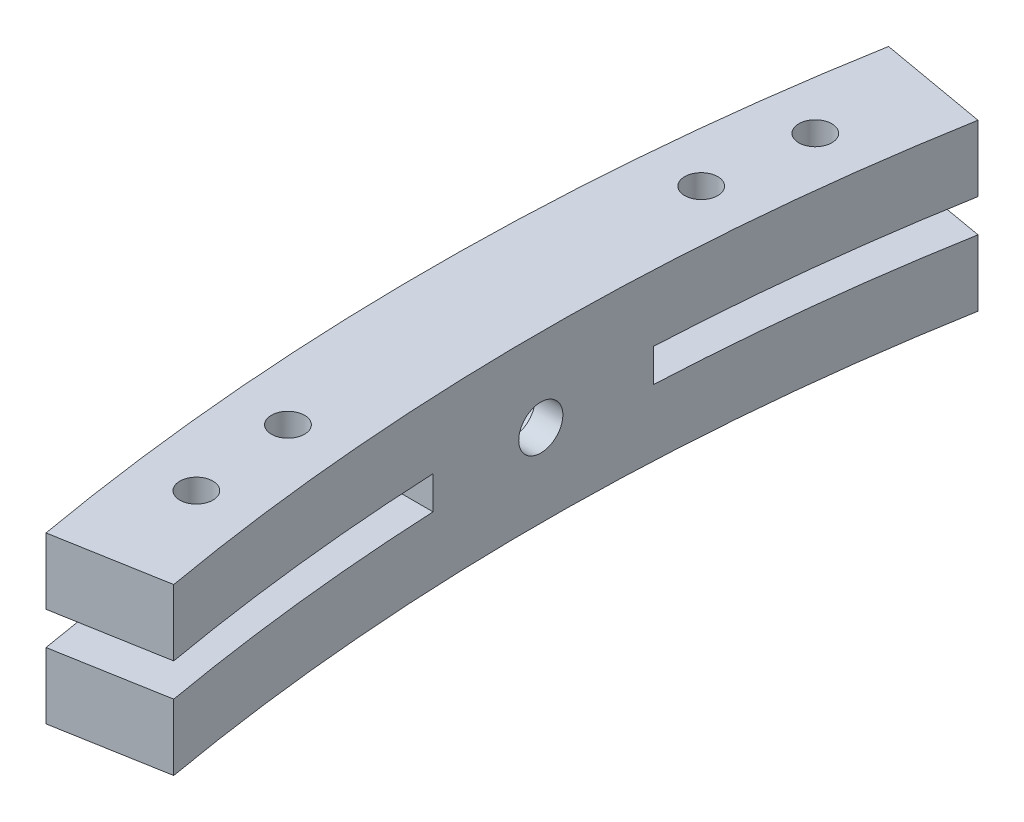
SolidWorks part; units mm, degrees
ref_plane "Front Plane" through (0, 0, 0) normal (0, 0, 1) x (1, 0, 0)
ref_plane "Top Plane" through (0, 0, 0) normal (0, 1, 0) x (1, 0, 0)
ref_plane "Right Plane" through (0, 0, 0) normal (1, 0, 0) x (0, 0, -1)
sketch "Sketch1" plane through (0, 0, 0) normal (0, 0, 1) x (1, 0, 0)
  line L0 (190, 0) -> (-190, 0) construction
  line L1 (0, 190) -> (0, -190) construction
  line L2 (0, 0) -> (-187.1135, 32.9932) construction
  line L3 (0, 0) -> (-187.1135, -32.9932) construction
  line L4 (-187.1135, 32.9932) -> (-196.9616, 34.7296)
  line L5 (-187.1135, -32.9932) -> (-196.9616, -34.7296)
  arc A0 (-187.1135, 32.9932) -> (-187.1135, -32.9932) centre (0, 0) ccw
  arc A1 (-196.9616, 34.7296) -> (-196.9616, -34.7296) centre (0, 0) ccw
  circle A3 centre (0, 0) radius 190 construction
  dimension "D1" = 380
  dimension "D2" = 10
  dimension "D3" = 20
sketch "Sketch9" plane through (0, 0, 0) normal (0, 1, 0) x (1, 0, 0)
  line L0 (0, 0) -> (-196.9616, 34.7296)
  line L1 (-200, 0) -> (200, 0) construction
  line L2 (0, 0) -> (-196.9616, -34.7296)
  circle A0 centre (0, 0) radius 195 construction
  circle A1 centre (0, 0) radius 195 construction
  circle A8 centre (0, 0) radius 200 construction
  circle A9 centre (0, 0) radius 190 construction
  circle A10 centre (0, 0) radius 200
  circle A11 centre (0, 0) radius 190
  dimension "D1" = 20
extrude "base" [suppressed] add sketch "Sketch9" along normal mid plane 15 contours A11 L0 A10 L2
sketch "Sketch11" [suppressed] plane through (0, 0, 0) normal (0, 1, 0) x (1, 0, 0)
  line L8 (-189.7367, -10) -> (-199.7498, -10) construction
  line L9 (-187.1135, -32.9932) -> (-196.9616, -34.7296) construction
  line L10 (-189.7367, 10) -> (-199.7498, 10) construction
  line L11 (-187.1135, 32.9932) -> (-196.9616, 34.7296) construction
  line L12 (-189.7367, -10) -> (-199.7498, -10)
  line L13 (-187.1135, -32.9932) -> (-196.9616, -34.7296)
  line L14 (-189.7367, 10) -> (-199.7498, 10)
  line L15 (-187.1135, 32.9932) -> (-196.9616, 34.7296)
  circle A14 centre (0, 0) radius 200 construction
  circle A15 centre (0, 0) radius 190 construction
  arc A16 (-196.9616, 34.7296) -> (-199.7498, 10) centre (0, 0) ccw
  arc A17 (-187.1135, 32.9932) -> (-189.7367, 10) centre (0, 0) ccw
  arc A18 (-199.7498, -10) -> (-196.9616, -34.7296) centre (0, 0) ccw
  arc A19 (-189.7367, -10) -> (-187.1135, -32.9932) centre (0, 0) ccw
extrude "Cut-Extrude8" [suppressed] cut sketch "Sketch11" along normal up to surface and the other way up to surface
sketch "Sketch12" plane through (0, 0, 0) normal (0, 1, 0) x (1, 0, 0)
  line L0 (-200, 0) -> (200, 0) construction
  line L1 (-200, 0) -> (200, 0) construction
  circle A0 centre (0, 0) radius 195 construction
  circle A1 centre (0, 0) radius 195 construction
  circle A2 centre (-193.3908, 25) radius 1.5
  circle A3 centre (-194.4222, 15) radius 1.5
  circle A4 centre (-194.4222, -15) radius 1.5
  circle A5 centre (-193.3908, -25) radius 1.5
  dimension "D1" = 3
  dimension "D2" = 30
  dimension "D3" = 50
extrude "Cut-Extrude9" [suppressed] cut sketch "Sketch12" against normal through all both and the other way through all
sketch "Sketch13" plane through (0, 0, 0) normal (0, 1, 0) x (1, 0, 0)
  line L2 (0, 0) -> (-216.6577, 38.2026)
  line L4 (-215, 0) -> (215, 0) construction
  line L5 (-215, 0) -> (215, 0) construction
  line L6 (0, 0) -> (-216.6577, -38.2026)
  line L7 (-209.7618, -10) -> (-219.7726, -10) construction
  line L8 (-209.7618, 10) -> (-219.7726, 10) construction
  line L9 (-209.7618, -10) -> (-219.7726, -10)
  line L10 (-209.7618, 10) -> (-219.7726, 10)
  circle A5 centre (0, 0) radius 215 construction
  circle A6 centre (0, 0) radius 220 construction
  circle A7 centre (0, 0) radius 210 construction
  circle A8 centre (0, 0) radius 220
  circle A9 centre (0, 0) radius 210
  dimension "D1" = 20
extrude "base2" add sketch "Sketch13" along normal mid plane 15 contours A9 L2 A8 L10 | A9 L10 A8 L9 | A9 L9 A8 L6
sketch "Sketch14" plane through (0, 0, 0) normal (0, 1, 0) x (1, 0, 0)
  line L0 (-209.7618, -10) -> (-219.7726, -10) construction
  line L1 (-209.7618, 10) -> (-219.7726, 10) construction
  line L2 (-209.7618, -10) -> (-219.7726, -10)
  line L3 (-209.7618, 10) -> (-219.7726, 10)
  line L4 (0, 0) -> (-216.6577, 38.2026) construction
  line L5 (0, 0) -> (-216.6577, -38.2026) construction
  line L6 (-206.8096, 36.4661) -> (-216.6577, 38.2026)
  line L7 (-206.8096, -36.4661) -> (-216.6577, -38.2026)
  arc A0 (-219.7726, -10) -> (-216.6577, -38.2026) centre (0, 0) ccw
  arc A1 (-209.7618, -10) -> (-206.8096, -36.4661) centre (0, 0) ccw
  circle A4 centre (0, 0) radius 220 construction
  circle A5 centre (0, 0) radius 210 construction
  arc A6 (-216.6577, 38.2026) -> (-219.7726, 10) centre (0, 0) ccw
  arc A7 (-206.8096, 36.4661) -> (-209.7618, 10) centre (0, 0) ccw
extrude "mount2" cut sketch "Sketch14" along normal up to surface and the other way up to surface
sketch "Sketch16" plane through (0, 0, 0) normal (0, 1, 0) x (1, 0, 0)
  line L0 (-214.1819, 18.7385) -> (0, 0) construction
  line L1 (0, 0) -> (-213.1606, 28.0631) construction
  line L3 (0, 0) -> (-215, 0) construction
  line L4 (-214.1819, -18.7385) -> (0, 0) construction
  line L5 (0, 0) -> (-213.1606, -28.0631) construction
  circle A0 centre (0, 0) radius 215 construction
  circle A1 centre (0, 0) radius 215 construction
  circle A2 centre (-213.1606, 28.0631) radius 1.5
  circle A3 centre (-214.1819, 18.7385) radius 1.5
  circle A4 centre (-214.1819, -18.7385) radius 1.5
  circle A5 centre (-213.1606, -28.0631) radius 1.5
  dimension "D1" = 3
  dimension "D2" = 10
  dimension "D3" = 15
extrude "mount hole2" cut sketch "Sketch16" against normal through all both and the other way through all
ref_plane "shaft" through (-215, 0, 0) normal (1, 0, 0) x (0, 0, -1)
sketch "Sketch17" plane through (-215, 0, 0) normal (1, 0, 0) x (0, 0, -1)
  circle A0 centre (0, 0) radius 2
  dimension "D1" = 4
extrude "shaft hole" cut sketch "Sketch17" along normal through all
sketch "Sketch18" plane through (0, 0, 0) normal (0, 1, 0) x (1, 0, 0)
  line L1 (-215, 0) -> (-212.5, 0)
  line L16 (-215, 0) -> (-215, 3.5)
  line L17 (-215, 3.5) -> (-212.5, 3.5)
  line L18 (-212.5, 0) -> (-212.5, 3.5)
  point P0 (-215, 0)
  dimension "D1" = 2.5
  dimension "D2" = 3.5
revolve "bearinghole" cut sketch "Sketch18" angle 360 about L5
sketch "Sketch6" plane through (0, 0, 0) normal (0, 0, 1) x (1, 0, 0)
  line L1 (-208.5097, 7.5) -> (-171.4903, 7.5)
  line L2 (-208.5097, 7.5) -> (-208.5097, -7.5)
  line L3 (-208.5097, -7.5) -> (-171.4903, -7.5)
  line L4 (-171.4903, 7.5) -> (-171.4903, -7.5)
  line L5 (-208.5097, 7.5) -> (-171.4903, -7.5) construction
  line L6 (-208.5097, -7.5) -> (-171.4903, 7.5) construction
  arc A0 (-196.9616, 34.7296) -> (-196.9616, -34.7296) centre (0, 0) ccw construction
  arc A1 (-187.1135, 32.9932) -> (-187.1135, -32.9932) centre (0, 0) ccw construction
  arc A2 (-196.9616, 34.7296) -> (-196.9616, -34.7296) centre (0, 0) ccw
  arc A3 (-187.1135, 32.9932) -> (-187.1135, -32.9932) centre (0, 0) ccw
  point P0 (-190, 0)
  dimension "D1" = 15
ref_plane "Plane1" through (-190, 0, 0) normal (1, 0, 0) x (0, 0, -1)
sketch "Sketch4" plane through (-190, 0, 0) normal (1, 0, 0) x (0, 0, -1)
  circle A0 centre (0, 0) radius 3
  dimension "D1" = 6
sketch "Sketch7" plane through (-190, 0, 0) normal (1, 0, 0) x (0, 0, -1)
  circle A0 centre (0, 0) radius 1.5
  dimension "D1" = 3
